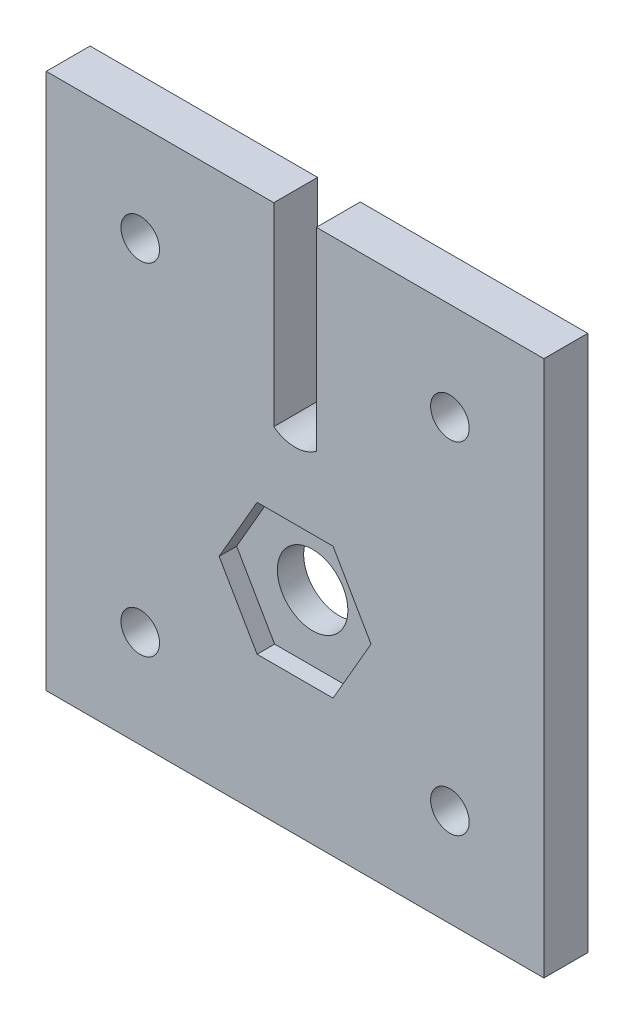
SolidWorks part; units mm, degrees
ref_plane "Front Plane" through (0, 0, 0) normal (0, 0, 1) x (1, 0, 0)
ref_plane "Top Plane" through (0, 0, 0) normal (0, 1, 0) x (1, 0, 0)
ref_plane "Right Plane" through (0, 0, 0) normal (1, 0, 0) x (0, 0, -1)
sketch "Sketch1" plane through (0, 0, 0) normal (0, 0, 1) x (1, 0, 0)
  line L0 (23.5034, -26.6844) -> (45.9189, -26.6844) construction
  line L1 (16.6987, 5.0709) -> (33.1687, 5.0709)
  line L2 (16.6987, 5.0709) -> (16.6987, -33.756)
  line L3 (16.6987, -33.756) -> (52.7236, -33.756)
  line L4 (52.7236, 5.0709) -> (52.7236, -33.756)
  line L5 (36.2536, 5.0709) -> (52.7236, 5.0709)
  line L6 (33.1687, -4.9034) -> (33.1687, 5.0709)
  line L7 (36.2536, -4.9034) -> (36.2536, 5.0709)
  line L8 (33.1687, -4.9034) -> (33.1687, -8.9713)
  line L10 (36.2536, -4.9034) -> (36.2536, -8.9713)
  line L11 (45.9189, -26.6844) -> (45.9189, -2.0006) construction
  line L12 (34.7111, -26.6844) -> (34.7111, -33.756) construction
  line L13 (45.9189, -14.3425) -> (52.7236, -14.3425) construction
  circle A0 centre (34.7111, -19.0791) radius 2.5527
  circle A1 centre (45.9189, -2.0006) radius 1.397
  circle A2 centre (23.5034, -2.0006) radius 1.397
  circle A3 centre (23.5034, -26.6844) radius 1.397
  circle A4 centre (45.9189, -26.6844) radius 1.397
  arc A5 (33.1687, -8.9713) -> (36.2536, -8.9713) centre (34.7111, -6.9374) ccw
extrude "Boss-Extrude1" add sketch "Sketch1" along normal blind 3.175
sketch "Sketch3" plane through (0, 0, 3.175) normal (0, 0, 1) x (1, 0, 0)
  line L6 (34.7111, -6.9374) -> (34.7111, -19.0791) construction
  line B0 (40.2104, -19.0791) -> (37.4608, -14.3166)
  line B1 (37.4608, -14.3166) -> (31.9615, -14.3166)
  line B2 (31.9615, -14.3166) -> (29.2119, -19.0791)
  line B3 (29.2119, -19.0791) -> (31.9615, -23.8416)
  line B4 (31.9615, -23.8416) -> (37.4608, -23.8416)
  line B5 (37.4608, -23.8416) -> (40.2104, -19.0791)
  circle B6 centre (34.7111, -19.0791) radius 4.7625 construction
sketch_block_instance "Block1-1"
sketch_block "Block1"
extrude "Cut-Extrude1" cut sketch "Sketch3" against normal blind 1.27
